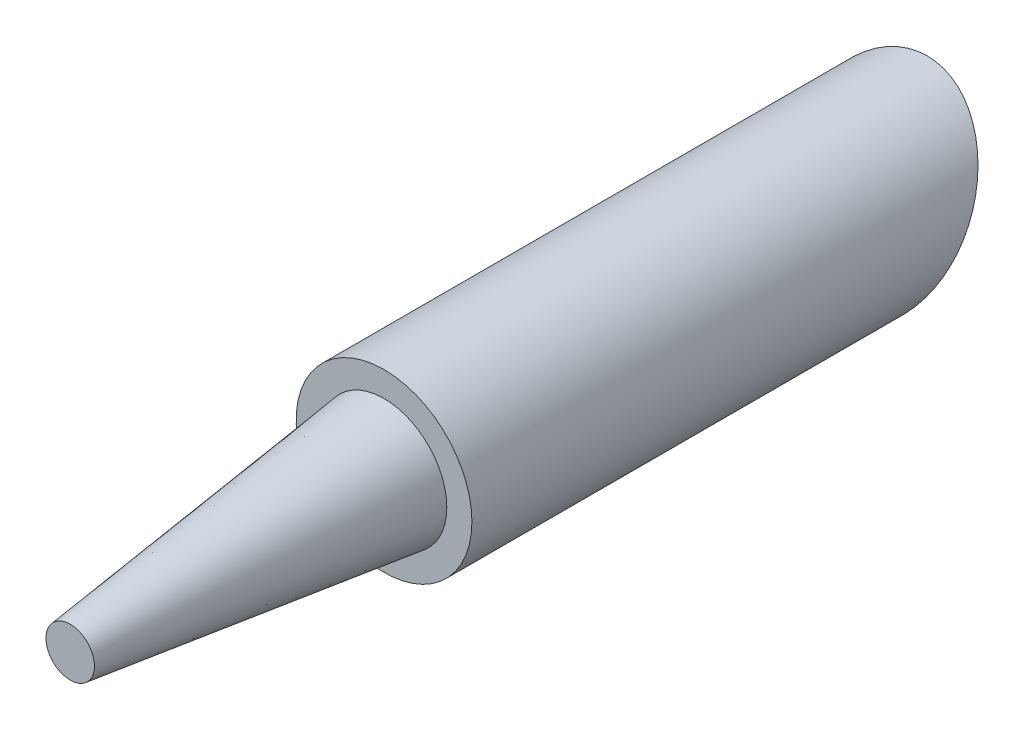
SolidWorks part; units mm, degrees
ref_plane "Front Plane" through (0, 0, 0) normal (0, 0, 1) x (1, 0, 0)
ref_plane "Top Plane" through (0, 0, 0) normal (0, 1, 0) x (1, 0, 0)
ref_plane "Right Plane" through (0, 0, 0) normal (1, 0, 0) x (0, 0, -1)
sketch "Sketch1" plane through (0, 0, 0) normal (0, 0, 1) x (1, 0, 0)
  circle A0 centre (0, 0) radius 17.78
  dimension "D1" = 35.56
extrude "Boss-Extrude1" add sketch "Sketch1" along normal blind 111.76
sketch "Sketch2" plane through (0, 0, 111.76) normal (0, 0, 1) x (1, 0, 0)
  circle A0 centre (0, 0) radius 12.7
  dimension "D1" = 25.4
extrude "Boss-Extrude2" add sketch "Sketch2" along normal blind 63.5 draft 7
sketch "Sketch4" plane through (0, 0, 0) normal (1, 0, 0) x (0, 0, -1)
  line L1 (16.51, 49.5792) -> (-26.4268, -24.7896)
  line L2 (-26.4268, -24.7896) -> (59.4468, -24.7896)
  line L3 (59.4468, -24.7896) -> (16.51, 49.5792)
  circle A0 centre (16.51, 0) radius 24.7896 construction
extrude "Cut-Extrude1" cut sketch "Sketch4" against normal through all both and the other way through all
